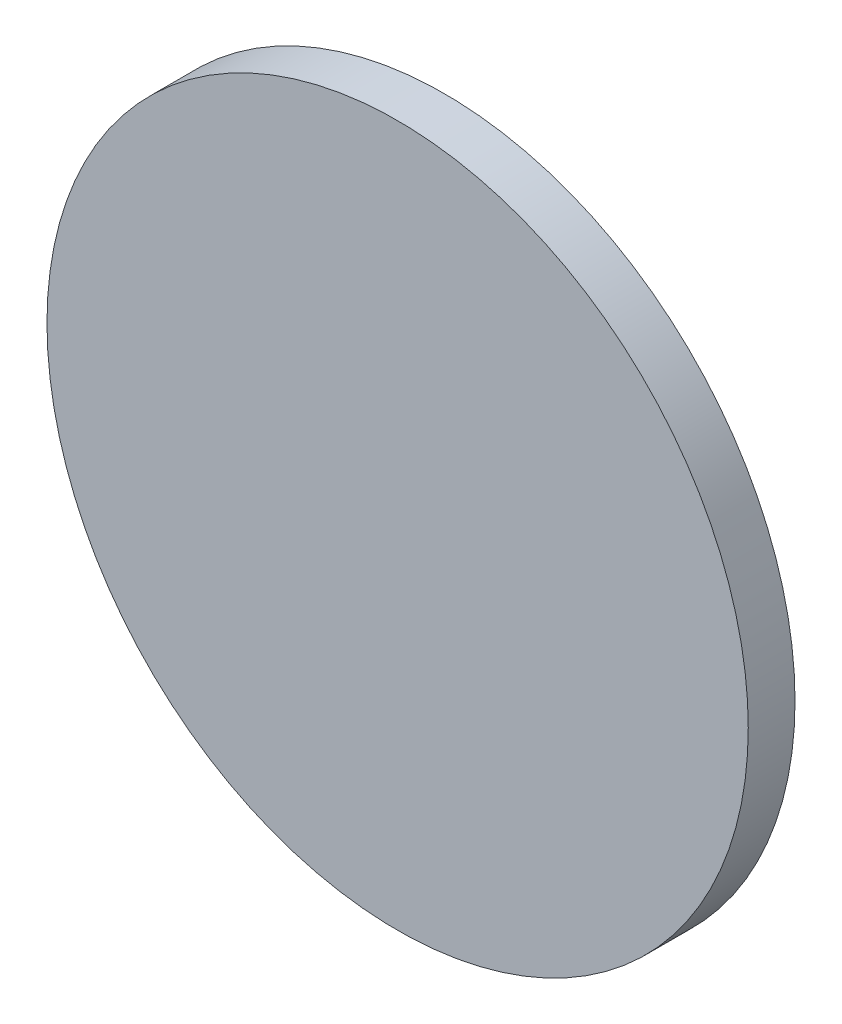
SolidWorks part; units mm, degrees
ref_plane "Front Plane" through (0, 0, 0) normal (0, 0, 1) x (1, 0, 0)
ref_plane "Top Plane" through (0, 0, 0) normal (0, 1, 0) x (1, 0, 0)
ref_plane "Right Plane" through (0, 0, 0) normal (1, 0, 0) x (0, 0, -1)
sketch "Sketch2" plane through (0, 0, 0) normal (0, 0, 1) x (1, 0, 0)
  circle A0 centre (0, 0) radius 30
  dimension "D1" = 60
extrude "Boss-Extrude1" add sketch "Sketch2" along normal blind 4.0012
